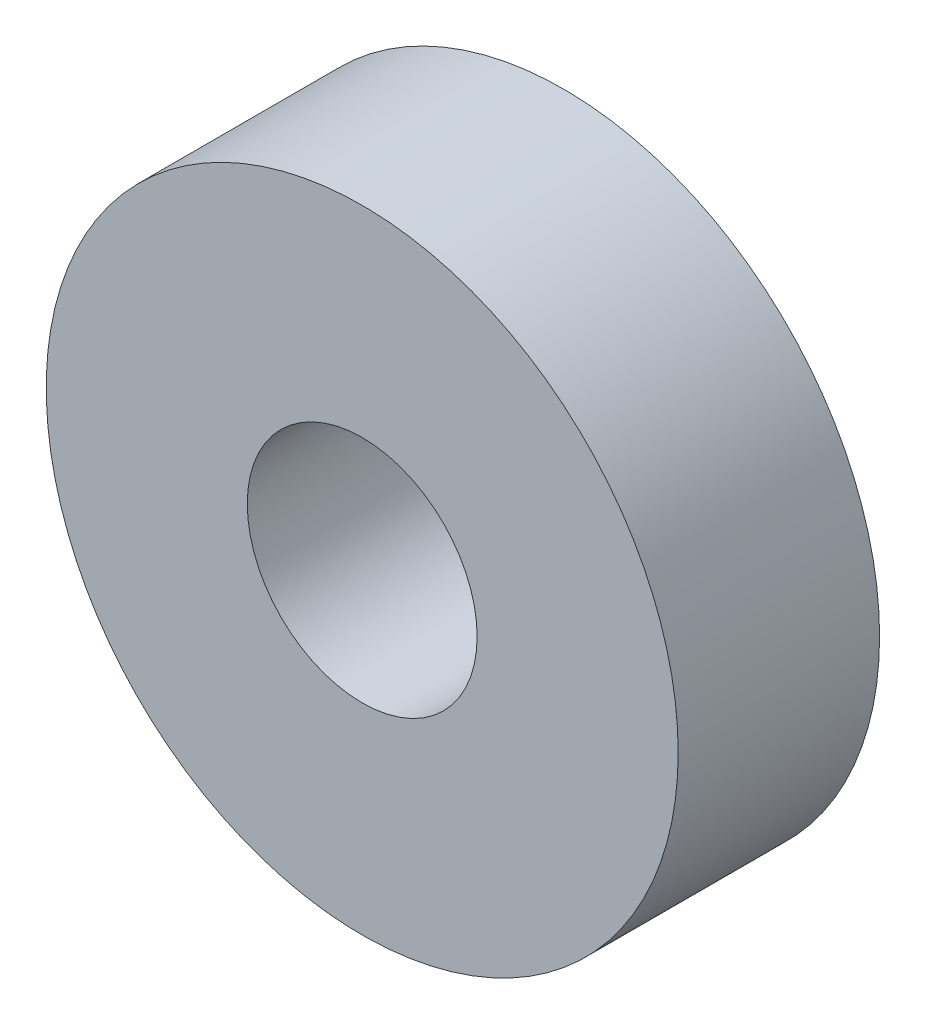
SolidWorks part; units mm, degrees
ref_plane "Front Plane" through (0, 0, 0) normal (0, 0, 1) x (1, 0, 0)
ref_plane "Top Plane" through (0, 0, 0) normal (0, 1, 0) x (1, 0, 0)
ref_plane "Right Plane" through (0, 0, 0) normal (1, 0, 0) x (0, 0, -1)
sketch "Sketch2" plane through (0, 0, 0) normal (0, 0, 1) x (1, 0, 0)
  circle A0 centre (0, 0) radius 10.9982
  dimension "D1" = 21.9964
sketch "Sketch3" plane through (0, 0, 0) normal (0, 0, 1) x (1, 0, 0)
  circle A0 centre (0, 0) radius 4.0005
  dimension "D1" = 8.001
extrude "Boss-Extrude1" add sketch "Sketch2" along normal mid plane 7.0104 contours A0
extrude "Cut-Extrude1" cut sketch "Sketch3" along normal mid plane 18.4404 contours A0
